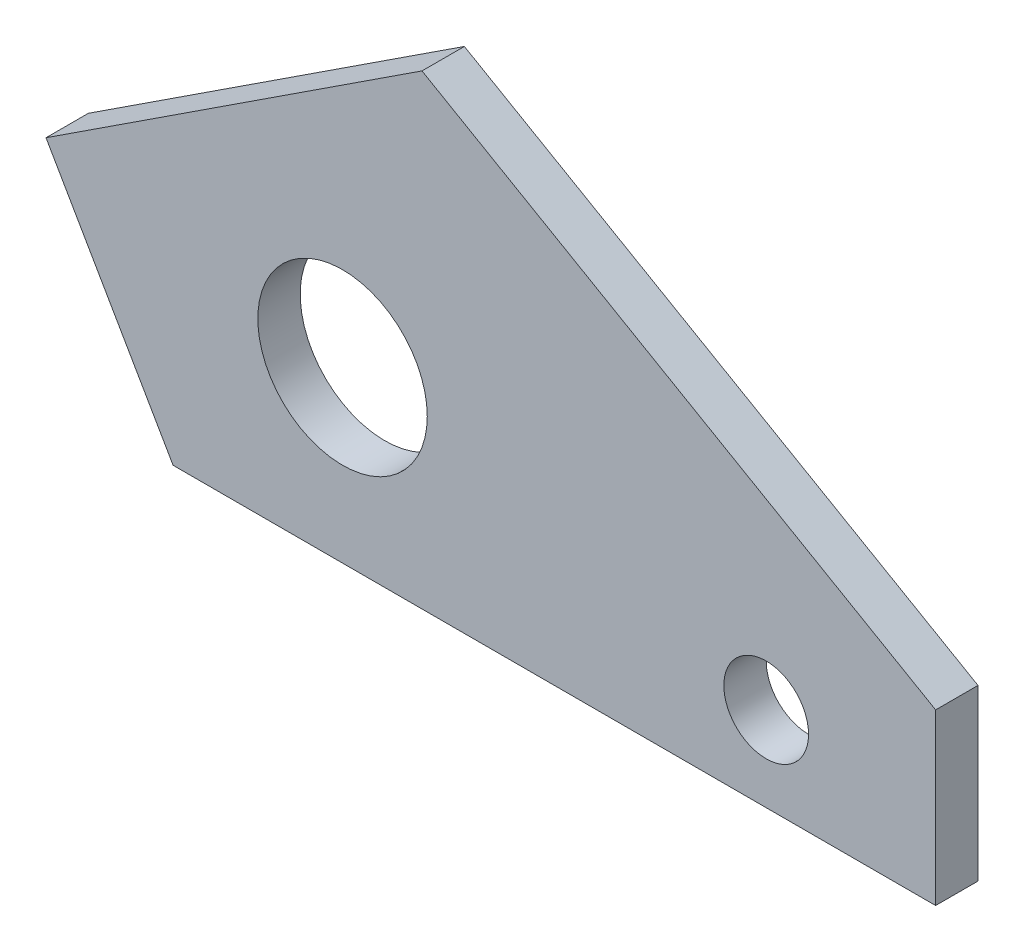
SolidWorks part; units mm, degrees
ref_plane "Front Plane" through (0, 0, 0) normal (0, 0, 1) x (1, 0, 0)
ref_plane "Top Plane" through (0, 0, 0) normal (0, 1, 0) x (1, 0, 0)
ref_plane "Right Plane" through (0, 0, 0) normal (1, 0, 0) x (0, 0, -1)
sketch "Sketch1" plane through (0, 0, 0) normal (0, 0, 1) x (1, 0, 0)
  line L0 (-79.5048, 69.85) -> (-2.5152, 25.4)
  line L1 (-2.5152, 25.4) -> (-2.5152, 0)
  line L2 (-2.5152, 0) -> (-116.8152, 0)
  line L3 (-116.8152, 0) -> (-135.8652, 32.9956)
  line L4 (-135.8652, 32.9956) -> (-79.5048, 69.85)
  dimension "D1" = 114.3
  dimension "D2" = 25.4
  dimension "D3" = 88.9
  dimension "D4" = 38.1
  dimension "D5" = 60
  dimension "D6" = 60
extrude "Boss-Extrude1" add sketch "Sketch1" along normal blind 6.35 contours L4 L0 L1 L2 L3
sketch "Sketch2" plane through (0, 0, 6.35) normal (0, 0, 1) x (1, 0, 0)
  line L0 (-2.5152, 0) -> (-116.8152, 0) construction
  line L1 (-2.5152, 25.4) -> (-2.5152, 0) construction
  circle A0 centre (-91.4152, 25.4) radius 12.7
  circle A1 centre (-27.9152, 12.7) radius 6.35
  point P8 (0, 0)
  point P10 (-28.4114, 11.3198)
  dimension "D1" = 25.4
  dimension "D4" = 12.7
  dimension "D6" = 12.7
  dimension "D2" = 25.4
  dimension "D3" = 88.9
  dimension "D5" = 25.4
extrude "Cut-Extrude1" cut sketch "Sketch2" against normal through all
